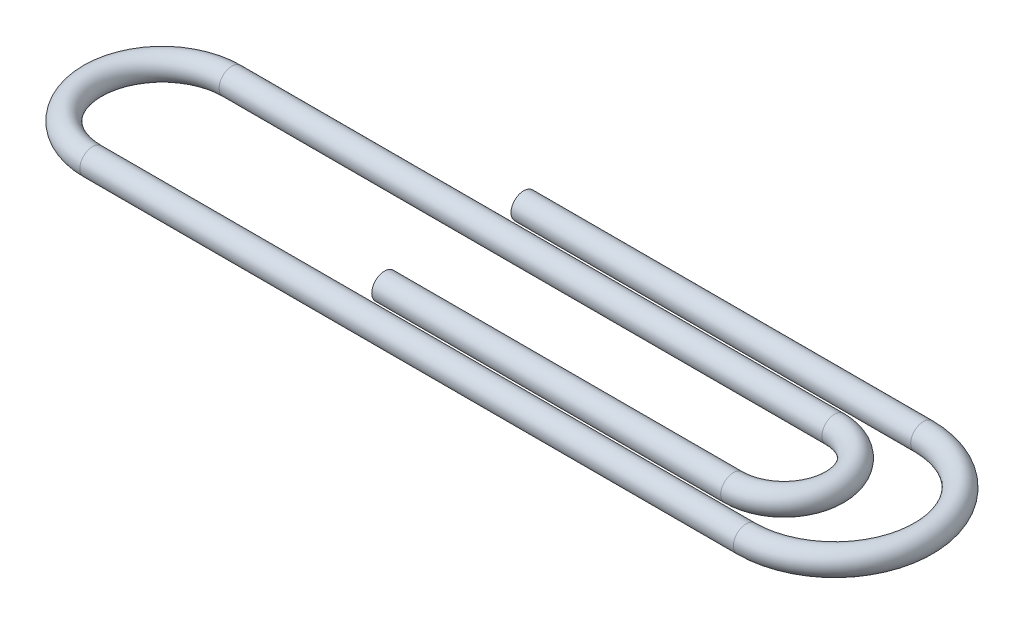
SolidWorks part; units mm, degrees
ref_plane "Front Plane" through (0, 0, 0) normal (0, 0, 1) x (1, 0, 0)
ref_plane "Top Plane" through (0, 0, 0) normal (0, 1, 0) x (1, 0, 0)
ref_plane "Right Plane" through (0, 0, 0) normal (1, 0, 0) x (0, 0, -1)
sketch "Sketch1" plane through (0, 0, 0) normal (0, 1, 0) x (1, 0, 0)
  line L0 (10, 4.25) -> (25.75, 4.25)
  line L1 (0, -2.75) -> (25.75, -2.75)
  line L2 (10, -1.25) -> (23.75, -1.25)
  line L3 (0, 2.75) -> (23.75, 2.75)
  line L5 (-68.3757, 2.75) -> (25.75, 2.75) construction
  line L6 (-68.3757, -1.25) -> (25.75, -1.25) construction
  line L8 (-68.3757, -2.75) -> (25.75, -2.75) construction
  line L9 (-68.3757, 4.25) -> (25.75, 4.25) construction
  arc A1 (25.75, -2.75) -> (25.75, 4.25) centre (25.75, 0.75) ccw
  arc A2 (23.75, -1.25) -> (23.75, 2.75) centre (23.75, 0.75) ccw
  arc A3 (0, 2.75) -> (0, -2.75) centre (0, 0) ccw
  point P11 (0, 0)
  point P15 (10.3241, 50.8709)
  dimension "D4" = 2.75
  dimension "D5" = 25.75
  dimension "D8" = 2
  dimension "D6" = 10
  dimension "D7" = 10
  dimension "D1" = 7
  dimension "D2" = 1.5
  dimension "D3" = 1.5
ref_plane "Plane1" through (10, 0, -4.25) normal (1, 0, 0) x (0, 0, -1)
sketch "Sketch2" plane through (10, 0, -4.25) normal (1, 0, 0) x (0, 0, -1)
  circle A0 centre (-0.0066, 0) radius 0.5
  dimension "D1" = 1
  dimension "D2" = 4.2434
sweep "Sweep1" add profiles "Sketch2" path "Sketch1"
